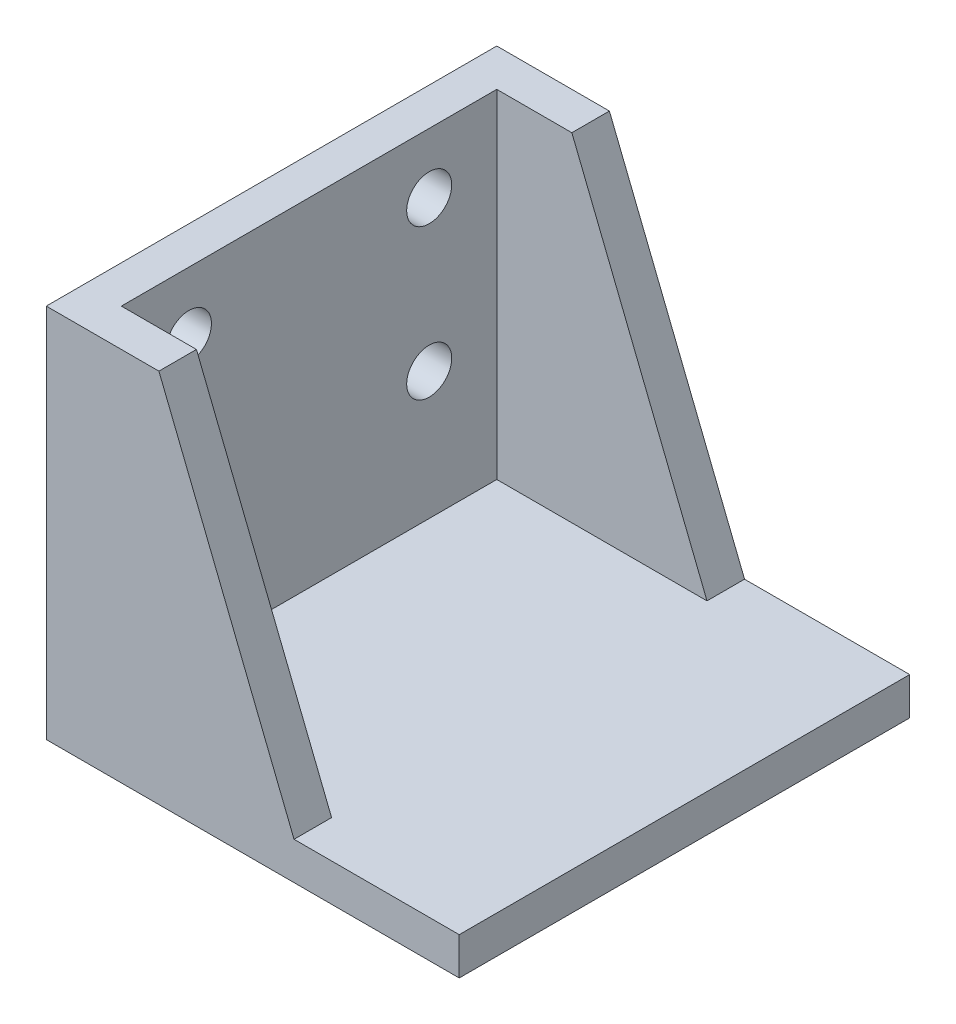
SolidWorks part; units mm, degrees
ref_plane "前视基准面" through (0, 0, 0) normal (0, 0, 1) x (1, 0, 0)
ref_plane "上视基准面" through (0, 0, 0) normal (0, 1, 0) x (1, 0, 0)
ref_plane "右视基准面" through (0, 0, 0) normal (1, 0, 0) x (0, 0, -1)
sketch "草图1" plane through (0, 0, 0) normal (0, 0, 1) x (1, 0, 0)
  line L4 (-11.4894, -7.1277) -> (-46.4894, -7.1277)
  line L5 (-46.4894, -7.1277) -> (-46.4894, 42.8723)
  line L6 (-46.4894, 42.8723) -> (-31.4894, 42.8723)
  line L7 (-31.4894, 42.8723) -> (-11.4894, -7.1277)
  dimension "D1" = 35
  dimension "D2" = 50
  dimension "D3" = 15
extrude "凸台-拉伸1" add sketch "草图1" along normal blind 60
sketch "草图2" plane through (0, 42.8723, 0) normal (0, 1, 0) x (1, 0, 0)
  line L0 (-41.4894, -5) -> (-6.8445, -5)
  line L1 (-6.8445, -5) -> (-6.8445, -55)
  line L2 (-6.8445, -55) -> (-41.4894, -55)
  line L3 (-41.4894, -55) -> (-41.4894, -5)
  line L4 (-46.4894, -60) -> (-46.4894, 0) construction
  line L5 (-31.4894, 0) -> (-46.4894, 0) construction
  line L6 (-31.4894, -60) -> (-46.4894, -60) construction
  dimension "D1" = 5
  dimension "D2" = 5
  dimension "D3" = 5
extrude "切除-拉伸1" cut sketch "草图2" against normal blind 45
sketch "草图3" plane through (0, -7.1277, 0) normal (0, -1, 0) x (1, 0, 0)
  line L0 (-28.9894, 60) -> (-28.9894, -8.8482) construction
  line L1 (-46.4894, 60) -> (-11.4894, 60) construction
  line L2 (-46.4894, 30) -> (-1.4335, 30) construction
  line L3 (-46.4894, 60) -> (-46.4894, 0) construction
  circle A0 centre (-35.4894, 48) radius 3
  circle A11 centre (-35.4894, 12) radius 3
  circle A12 centre (-19.4894, 12) radius 2.5
  circle A13 centre (-19.4894, 48) radius 2.5
  dimension "D1" = 6
  dimension "D5" = 16
  dimension "D2" = 11
  dimension "D3" = 18
  dimension "D4" = 16
extrude "切除-拉伸2" cut sketch "草图3" against normal through all
sketch "草图4" plane through (-46.4894, 0, 0) normal (-1, 0, 0) x (0, 0, 1)
  line L0 (30, 42.8723) -> (30, -20.5761) construction
  line L1 (60, 42.8723) -> (0, 42.8723) construction
  circle A0 centre (14, 34.8723) radius 3
  circle A1 centre (46, 34.8723) radius 3
  circle A2 centre (14, 14.8723) radius 3
  circle A3 centre (46, 14.8723) radius 3
  dimension "D1" = 6
  dimension "D2" = 16
  dimension "D3" = 8
  dimension "D4" = 20
  dimension "D5" = 20
extrude "切除-拉伸3" cut sketch "草图4" against normal through all
sketch "草图5" plane through (-41.4894, 0, 0) normal (1, 0, 0) x (0, 0, -1)
  line L0 (0, -7.1277) -> (-60, -7.1277)
  line L1 (-60, -7.1277) -> (-60, -2.1277)
  line L2 (-60, -7.1277) -> (-60, 42.8723) construction
  line L3 (-60, -2.1277) -> (0, -2.1277)
  line L4 (0, -7.1277) -> (0, 42.8723) construction
  line L5 (0, -2.1277) -> (0, -7.1277)
extrude "凸台-拉伸2" add sketch "草图5" along normal blind 50
